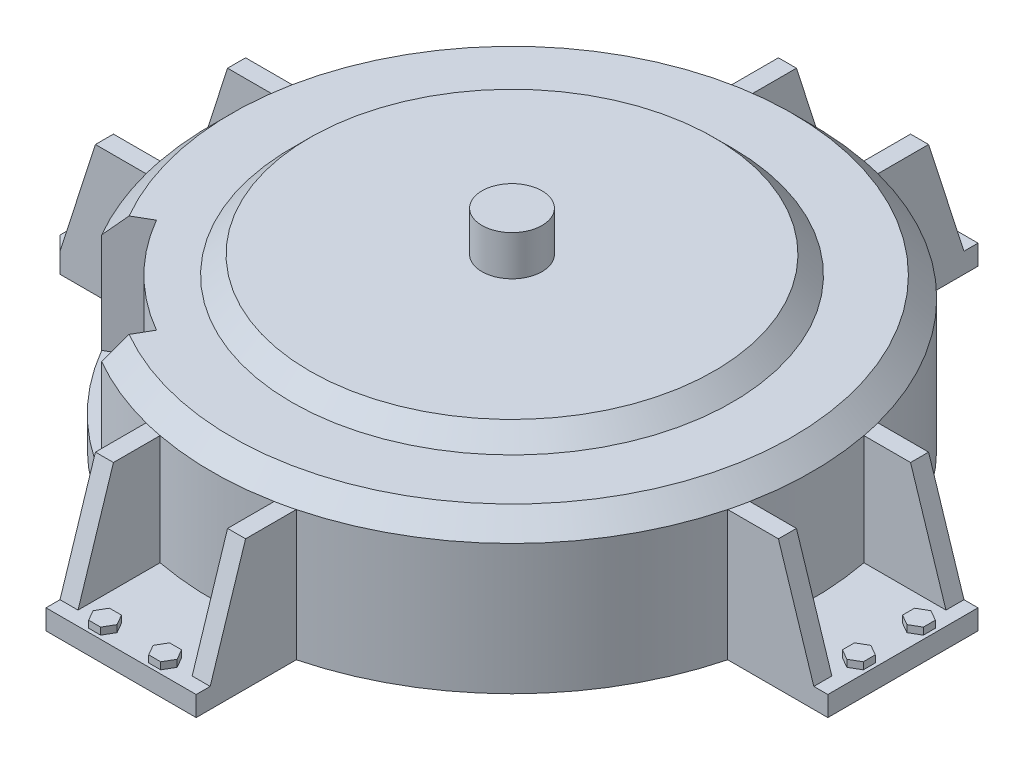
SolidWorks part; units mm, degrees
ref_plane "Front Plane" through (0, 0, 0) normal (0, 0, 1) x (1, 0, 0)
ref_plane "Top Plane" through (0, 0, 0) normal (0, 1, 0) x (1, 0, 0)
ref_plane "Right Plane" through (0, 0, 0) normal (1, 0, 0) x (0, 0, -1)
sketch "Sketch2" plane through (0, 0, 0) normal (0, 1, 0) x (1, 0, 0)
  circle A0 centre (0, 0) radius 150
  dimension "D1" = 300
extrude "Boss-Extrude1" add sketch "Sketch2" along normal blind 75
chamfer "Chamfer1" distance 10 angle 45 1 edges at (0, 75, 150)
sketch "Sketch4" plane through (0, 75, 0) normal (0, 1, 0) x (1, 0, 0)
sketch "Sketch3" plane through (0, 75, 0) normal (0, 1, 0) x (1, 0, 0)
  line L0 (-1.7511, 0) -> (-255.0713, 0) construction
  line L1 (-145.2369, 37.5) -> (-195.2369, 37.5)
  line L2 (-195.2369, 37.5) -> (-195.2369, -37.5)
  line L3 (-195.2369, -37.5) -> (-145.2369, -37.5)
  circle A0 centre (0, 0) radius 150 construction
  arc A1 (-145.2369, 37.5) -> (-145.2369, -37.5) centre (0, 0) ccw
  dimension "D1" = 75
  dimension "D2" = 50
extrude "Boss-Extrude2" add sketch "Sketch3" along normal blind 10 from offset 75 contours A1 L3 L2 L1 offset against normal yes
chamfer "Chamfer2" distance 7 angle 45 2 edges at (-195.2369, 5, -37.5) (-195.2369, 5, 37.5)
sketch "Sketch5" plane through (0, 0, 37.5) normal (0, 0, 1) x (1, 0, 0)
  line L0 (-145.2369, 10) -> (-145.2369, 65)
  line L1 (-150, 65) -> (150, 65) construction
  line L2 (-145.2369, 65) -> (-170.5569, 65)
  line L3 (-170.5569, 65) -> (-188.2369, 10)
  line L4 (-188.2369, 10) -> (-145.2369, 10)
  dimension "D1" = 17.68
  dimension "D2" = 25.32
extrude "Boss-Extrude3" add sketch "Sketch5" against normal blind 9
sketch "Sketch6" plane through (0, 10, 0) normal (0, 1, 0) x (1, 0, 0)
  line L0 (-149.988, -1.8949) -> (-236.8316, -1.8949) construction
  line L1 (-188.2369, 37.5) -> (-188.2369, -37.5) construction
  line L3 (-183.0407, -18) -> (-183.0407, -12)
  line L4 (-183.0407, -12) -> (-188.2369, -9)
  line L5 (-188.2369, -9) -> (-193.433, -12)
  line L6 (-193.433, -12) -> (-193.433, -18)
  line L7 (-193.433, -18) -> (-188.2369, -21)
  line L8 (-188.2369, -21) -> (-183.0407, -18)
  arc A0 (-145.2369, 37.5) -> (-147.2676, -28.5) centre (0, 0) ccw construction
  circle A1 centre (-188.2369, -15) radius 5.1962 construction
  dimension "D1" = 6
  dimension "D2" = 13.5
extrude "Boss-Extrude4" add sketch "Sketch6" along normal blind 3.5
mirror "Mirror1" about plane through (0, 0, 0) normal (0, 0, 1) of "Boss-Extrude4", "Boss-Extrude3"
pattern_circular "CirPattern1" count 4 over 360 about axis through (0, 0, 0) along (0, 1, 0) of "Boss-Extrude2", "Boss-Extrude3", "Boss-Extrude4", "Mirror1"
sketch "Sketch7" plane through (0, 75, 0) normal (0, 1, 0) x (1, 0, 0)
  line L0 (0, 0) -> (0, -221.6468) construction
  line L1 (0, -221.6468) -> (0, 226.7361) construction
  line L2 (0, 0) -> (-332.9228, 0) construction
  line L3 (-332.9228, 0) -> (332.2898, 0) construction
  line L4 (-112.5833, -65) -> (-129.9038, -75)
  line L5 (-65, -112.5833) -> (-75, -129.9038)
  arc A0 (0, -130) -> (-130, 0) centre (0, 0) ccw
  arc A1 (-112.5833, -65) -> (-65, -112.5833) centre (0, 0) ccw
  arc A3 (-145.2369, -37.5) -> (-37.5, -145.2369) centre (0, 0) ccw construction
  arc A6 (0, -140) -> (-140, 0) centre (0, 0) ccw
  arc A7 (-129.9038, -75) -> (-75, -129.9038) centre (0, 0) ccw
  circle M3 centre (0, 0) radius 140
  dimension "D1" = 260
  dimension "D2" = 30
  dimension "D3" = 30
extrude "Cut-Extrude2" cut sketch "Sketch7" against normal blind 60 contours L4 A7 L5 M3 | A1 L4 L5 M3
sketch "Sketch8" plane through (0, 75, 0) normal (0, 1, 0) x (1, 0, 0)
  circle A0 centre (0, 0) radius 110
  dimension "D1" = 220
extrude "Boss-Extrude5" add sketch "Sketch8" along normal blind 9 draft 45 contours A0
sketch "Sketch9" plane through (0, 84, 0) normal (0, 1, 0) x (1, 0, 0)
  circle A0 centre (0, 0) radius 15
  dimension "D1" = 30
extrude "Boss-Extrude6" add sketch "Sketch9" along normal blind 20
